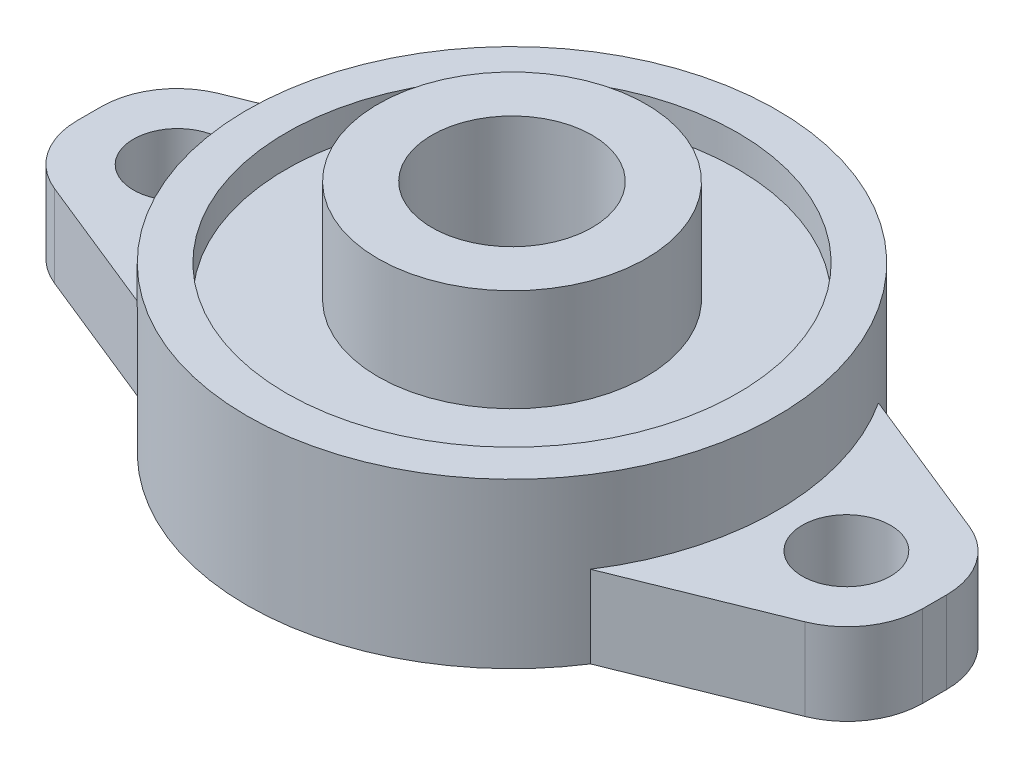
SolidWorks part; units mm, degrees
ref_plane "Front Plane" through (0, 0, 0) normal (0, 0, 1) x (1, 0, 0)
ref_plane "Top Plane" through (0, 0, 0) normal (0, 1, 0) x (1, 0, 0)
ref_plane "Right Plane" through (0, 0, 0) normal (1, 0, 0) x (0, 0, -1)
sketch "Sketch1" plane through (0, 0, 0) normal (0, 1, 0) x (1, 0, 0)
  line L4 (-33.5, 0) -> (-33.5, 5)
  line L5 (-33.5, 0) -> (-33.5, -5)
  line L6 (33.5, 0) -> (33.5, 5)
  line L7 (33.5, 0) -> (33.5, -5)
  line L8 (-33.5, 5) -> (-17.6294, 11.4121)
  line L9 (-33.5, -5) -> (-17.6294, -11.4121)
  line L10 (33.5, 5) -> (17.6294, 11.4121)
  line L11 (33.5, -5) -> (17.6294, -11.4121)
  circle A0 centre (0, 0) radius 6.35
  circle A1 centre (26.5, 0) radius 3.5
  circle A2 centre (-26.5, 0) radius 3.5
  circle A3 centre (0, 0) radius 21.0008
extrude "Boss-Extrude1" add sketch "Sketch1" along normal blind 6.5 contours A3 L8 L4 L5 L9 A2 | A3 A0 | A3 L11 L7 L6 L10 A1
sketch "Sketch2" plane through (0, 6.5, 0) normal (0, 1, 0) x (1, 0, 0)
  circle A0 centre (0, 0) radius 21.0008
  circle A1 centre (0, 0) radius 17.8859
extrude "Boss-Extrude2" add sketch "Sketch2" along normal blind 6.5
sketch "Sketch3" plane through (0, 6.5, 0) normal (0, 1, 0) x (1, 0, 0)
  circle A0 centre (0, 0) radius 10.6182
  circle A1 centre (0, 0) radius 6.35
extrude "Boss-Extrude3" add sketch "Sketch3" along normal blind 12.1
sketch "Sketch4" plane through (0, 6.5, 0) normal (0, 1, 0) x (1, 0, 0)
  circle A0 centre (0, 0) radius 10.6182
  circle A1 centre (0, 0) radius 17.8859
extrude "Boss-Extrude5" add sketch "Sketch4" along normal blind 4
fillet "Fillet1" radius 6 4 edges at (33.5, 3.25, 5) (33.5, 3.25, -5) (-33.5, 3.25, 5) (-33.5, 3.25, -5)
